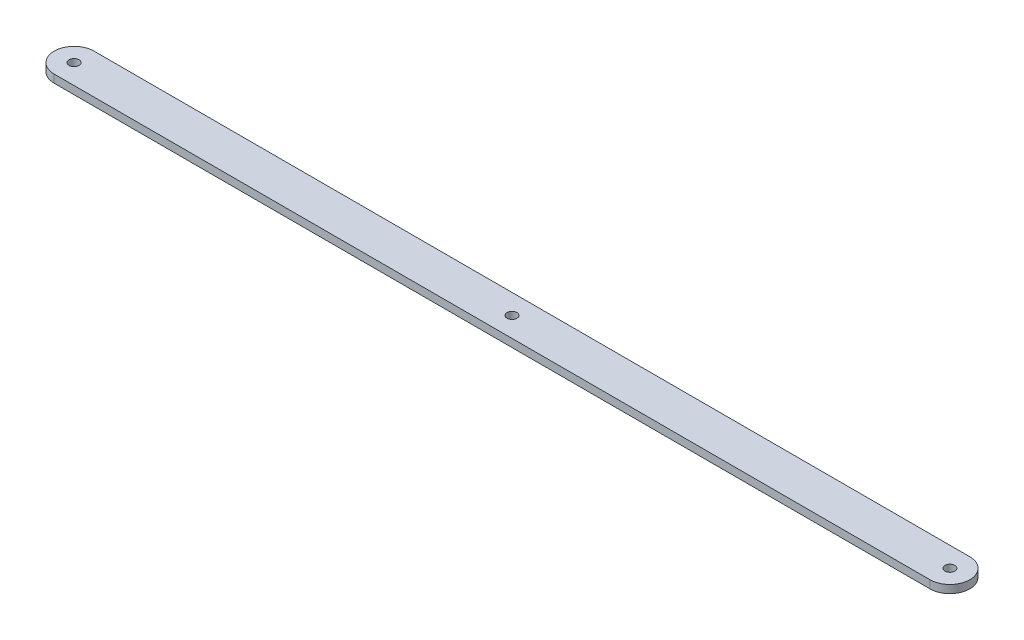
SolidWorks part; units mm, degrees
material "Plain Carbon Steel"
ref_plane "Front Plane" through (0, 0, 0) normal (0, 0, 1) x (1, 0, 0)
ref_plane "Top Plane" through (0, 0, 0) normal (0, 1, 0) x (1, 0, 0)
ref_plane "Right Plane" through (0, 0, 0) normal (1, 0, 0) x (0, 0, -1)
sketch "Sketch1" plane through (0, 0, 0) normal (0, 1, 0) x (1, 0, 0)
  line L0 (-550, 0) -> (0, 0) construction
  line L1 (-550, 25) -> (550, 25)
  line L2 (-550, 25) -> (-550, -25) construction
  line L3 (-550, -25) -> (550, -25)
  line L4 (550, 25) -> (550, -25) construction
  line L5 (0, 0) -> (550, 0) construction
  arc A0 (-550, -25) -> (-550, 25) centre (-550, 0) cw
  arc A1 (550, 25) -> (550, -25) centre (550, 0) cw
  circle A2 centre (-550, 0) radius 6.25
  circle A3 centre (550, 0) radius 6.25
  dimension "D1" = 12.5
  dimension "D2" = 1100
  dimension "D3" = 50
extrude "Boss-Extrude1" add sketch "Sketch1" along normal blind 10
sketch "Sketch2" plane through (0, 10, 0) normal (0, 1, 0) x (1, 0, 0)
  circle A0 centre (0, 0) radius 6.25
  dimension "D1" = 12.5
extrude "Cut-Extrude1" cut sketch "Sketch2" against normal through all
